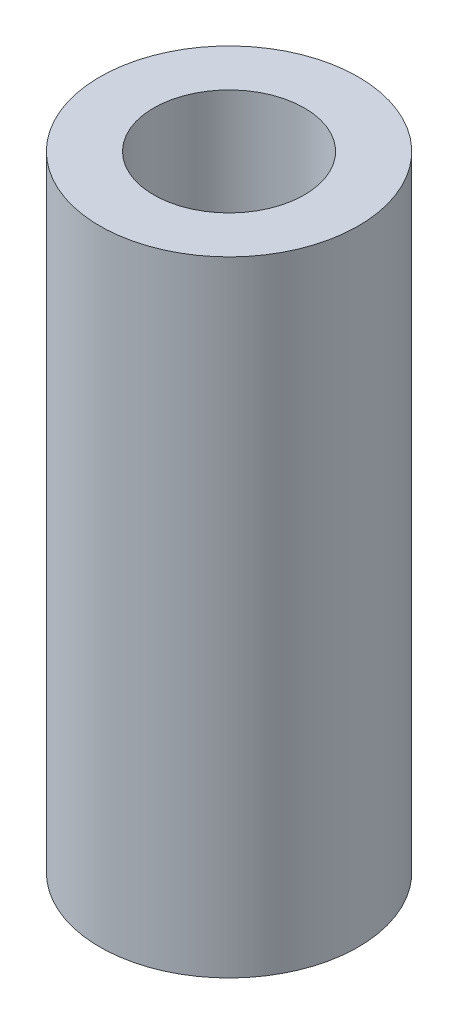
SolidWorks part; units mm, degrees
ref_plane "Front Plane" through (0, 0, 0) normal (0, 0, 1) x (1, 0, 0)
ref_plane "Top Plane" through (0, 0, 0) normal (0, 1, 0) x (1, 0, 0)
ref_plane "Right Plane" through (0, 0, 0) normal (1, 0, 0) x (0, 0, -1)
sketch "Sketch1" plane through (0, 0, 0) normal (0, 1, 0) x (1, 0, 0)
  circle A0 centre (0, 0) radius 3.5
  circle A1 centre (0, 0) radius 6
  dimension "D1" = 12
  dimension "D2" = 7
extrude "Boss-Extrude1" add sketch "Sketch1" along normal blind 29
